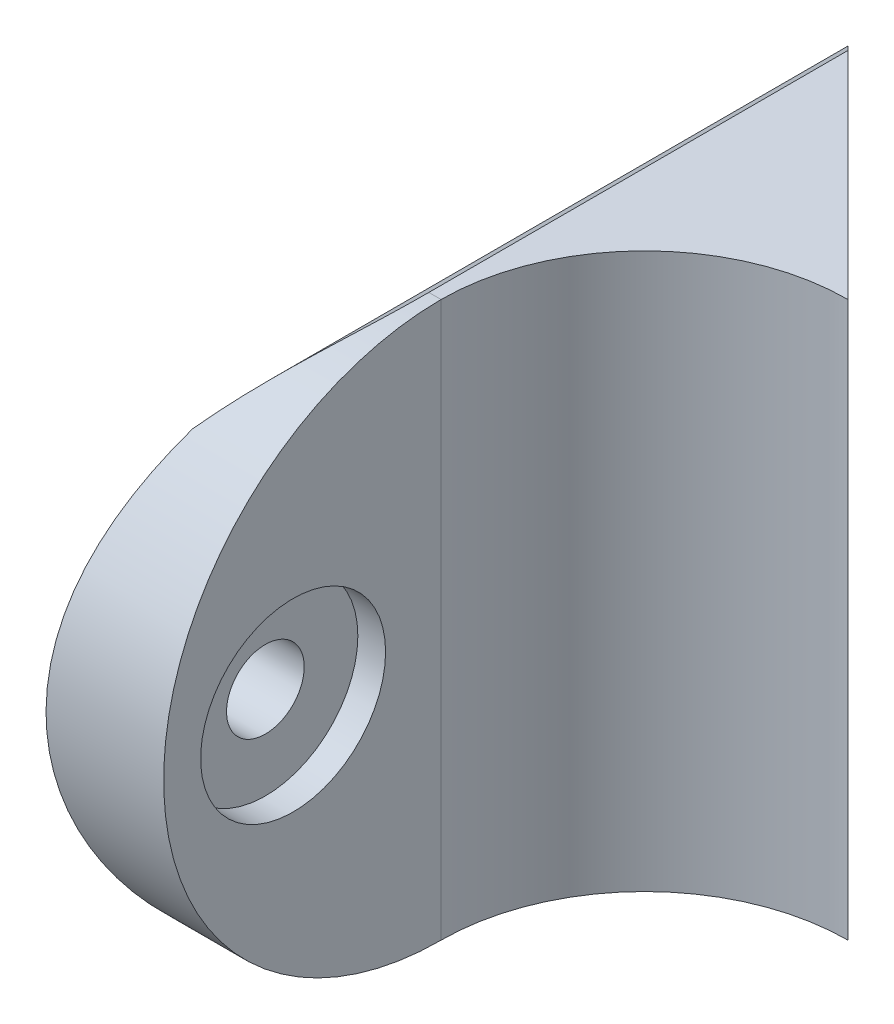
SolidWorks part; units mm, degrees
ref_plane "Front" through (0, 0, 0) normal (0, 0, 1) x (1, 0, 0)
ref_plane "Top" through (0, 0, 0) normal (0, 1, 0) x (1, 0, 0)
ref_plane "Right" through (0, 0, 0) normal (1, 0, 0) x (0, 0, -1)
sketch "Sketch1" plane through (0, 0, 0) normal (0, 0, 1) x (1, 0, 0)
  line L8 (-15, -15) -> (15, 15) construction
  line L9 (-15, 15) -> (15, -15) construction
  line L10 (-11.6619, -15) -> (11.6619, -15)
  line L12 (11.6619, 15) -> (-11.6619, 15)
  line L13 (0, 0) -> (0, -5.2602) construction
  circle A0 centre (0, 0) radius 19 construction
  arc A2 (-15, 11.6619) -> (-11.6619, 15) centre (0, 0) cw
  arc A3 (11.6619, 15) -> (15, 11.6619) centre (0, 0) cw
  arc A4 (15, -11.6619) -> (11.6619, -15) centre (0, 0) cw
  arc A5 (-11.6619, -15) -> (-15, -11.6619) centre (0, 0) cw
  arc A6 (15, 11.6619) -> (15, -11.6619) centre (-12.6351, 0) cw
  arc A7 (-15, 11.6619) -> (-15, -11.6619) centre (12.6351, 0) ccw
extrude "Boss-Extrude1" add sketch "Sketch1" along normal blind 50
sketch "Sketch2" plane through (0, 0, 0) normal (0, 1, 0) x (1, 0, 0)
  line L1 (-11, -35) -> (-11, -50)
  line L2 (-11, -50) -> (11, -50)
  line L3 (11, -50) -> (11, -35)
  circle A0 centre (0, -35) radius 11 construction
  arc A1 (11, -35) -> (-11, -35) centre (0, -35) ccw
extrude "Cut-Extrude1" cut sketch "Sketch2" against normal through all both and the other way through all
sketch "Sketch3" plane through (0, 0, 0) normal (0, 0, -1) x (-1, 0, 0)
  circle A0 centre (0, 0) radius 11.25
extrude "Cut-Extrude2" cut sketch "Sketch3" against normal blind 7
sketch "Sketch4" plane through (0, 0, 0) normal (0, 1, 0) x (1, 0, 0)
  line L0 (0, 0) -> (0, -18) construction
  line L2 (11.25, 0) -> (11.25, -7) construction
  line L3 (11.25, -7) -> (0, -7) construction
  line L4 (0, -7) -> (9, -7)
  line L5 (9, -7) -> (0, -9)
  line L6 (0, -9) -> (0, -7)
revolve "Cut-Revolve1" cut sketch "Sketch4" angle 360 about L6
sketch "Sketch5" plane through (11, 0, 0) normal (-1, 0, 0) x (0, 0, 1)
  circle A0 centre (43, 0) radius 2
extrude "Cut-Extrude3" cut sketch "Sketch5" against normal blind 3 and the other way blind 24
sketch "Sketch7" plane through (0, 0, 0) normal (1, 0, 0) x (0, 0, -1)
  line L0 (0, 0) -> (-28.2793, 0) construction
  circle A0 centre (-18, 6) radius 2.5
  circle A1 centre (-18, -6) radius 2.5
  dimension "D1" = 6
  dimension "D2" = 6
sketch "Sketch6" plane through (0, 0, 0) normal (0, 1, 0) x (1, 0, 0)
  line L0 (0, -24) -> (-19.5043, -4.4957)
  line L3 (0, -24) -> (0, -52.449)
  line L5 (-19.5043, -4.4957) -> (-19.5043, 1.2231)
  line L6 (-19.5043, 1.2231) -> (17.9942, 1.2231)
  line L7 (17.9942, 1.2231) -> (17.9942, -52.449)
  line L8 (17.9942, -52.449) -> (0, -52.449)
  arc A2 (11, -35) -> (-11, -35) centre (0, -35) ccw construction
extrude "Cut-Extrude4" cut sketch "Sketch6" against normal through all both and the other way through all
extrude "Cut-Extrude5" cut sketch "Sketch7" against normal blind 15 and the other way blind 3
sketch "Sketch9" plane through (-15, 0, 0) normal (-1, 0, 0) x (0, 0, 1)
  line L0 (13, 6) -> (13, -6)
  line L1 (23, -6) -> (23, 6)
  circle A0 centre (18, 6) radius 5 construction
  circle A1 centre (18, -6) radius 5 construction
  arc A2 (13, -6) -> (23, -6) centre (18, -6) ccw
  arc A3 (23, 6) -> (13, 6) centre (18, 6) ccw
extrude "Cut-Extrude7" cut sketch "Sketch9" against normal blind 1 and the other way blind 10
sketch "Sketch10" plane through (-11, 0, 0) normal (1, 0, 0) x (0, 0, -1)
  line L0 (-35, 15) -> (-35, 16.5805)
  line L1 (-35, 16.5805) -> (-52.0357, 16.5805)
  line L2 (-52.0357, 16.5805) -> (-52.0357, -15.9)
  line L3 (-52.0357, -15.9) -> (-35, -15.9)
  line L4 (-35, -15.9) -> (-35, -15)
  arc A0 (-35, 15) -> (-35, -15) centre (-35, 0) ccw
  point P9 (0, 0)
  point P10 (0, 0)
  point P11 (-35, 15)
  point P13 (-35, -15)
extrude "Cut-Extrude8" cut sketch "Sketch10" against normal blind 10
sketch "Sketch11" plane through (-11, 0, 0) normal (1, 0, 0) x (0, 0, -1)
  circle A0 centre (-43, 0) radius 2.1
  arc A1 (-35, 15) -> (-35, -15) centre (-35, 0) ccw construction
  point P5 (-50, 0)
  dimension "D1" = 7
extrude "Cut-Extrude9" cut sketch "Sketch11" against normal blind 10
sketch "Sketch12" plane through (-11, 0, 0) normal (1, 0, 0) x (0, 0, -1)
  circle A0 centre (-43, 0) radius 5
extrude "Cut-Extrude10" cut sketch "Sketch12" against normal blind 1.5
